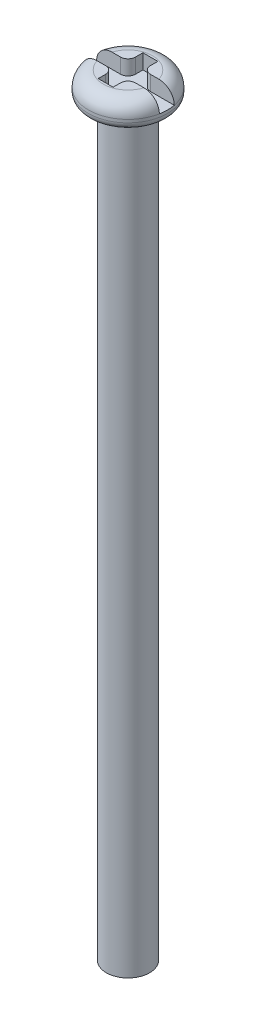
SolidWorks part; units mm, degrees
material "1060 合金"
ref_plane "前视基准面" through (0, 0, 0) normal (0, 0, 1) x (1, 0, 0)
ref_plane "上视基准面" through (0, 0, 0) normal (0, 1, 0) x (1, 0, 0)
ref_plane "右视基准面" through (0, 0, 0) normal (1, 0, 0) x (0, 0, -1)
sketch "草图1" plane through (0, 0, 0) normal (0, 1, 0) x (1, 0, 0)
  circle A0 centre (0, 0) radius 1.45
  dimension "D1" = 2.9
extrude "凸台-拉伸1" add sketch "草图1" along normal blind 50
cosmetic thread "装饰螺纹线1" parameters "D1"=49.5, "D2"=2.013
sketch "草图2" plane through (0, 50, 0) normal (0, 1, 0) x (1, 0, 0)
  circle A0 centre (0, 0) radius 2.65
  dimension "D1" = 5.3
extrude "凸台-拉伸2" add sketch "草图2" along normal blind 1.7
sketch "草图3" plane through (0, 51.7, 0) normal (0, 1, 0) x (1, 0, 0)
  line L1 (-3, 0.5) -> (3, 0.5)
  line L2 (-3, 0.5) -> (-3, -0.5)
  line L3 (-3, -0.5) -> (3, -0.5)
  line L4 (3, 0.5) -> (3, -0.5)
  line L5 (-3, 0.5) -> (3, -0.5) construction
  line L6 (-3, -0.5) -> (3, 0.5) construction
  line L7 (-0.5, 1.5) -> (0.5, 1.5)
  line L8 (-0.5, 1.5) -> (-0.5, -1.5)
  line L9 (-0.5, -1.5) -> (0.5, -1.5)
  line L10 (0.5, 1.5) -> (0.5, -1.5)
  line L11 (-0.5, 1.5) -> (0.5, -1.5) construction
  line L12 (-0.5, -1.5) -> (0.5, 1.5) construction
  point P0 (0, 0)
  point P6 (0, 0)
  circle M9 centre (0, 0) radius 2.65
  dimension "D1" = 1
  dimension "D2" = 6
  dimension "D3" = 1
  dimension "D4" = 3
extrude "切除-拉伸1" cut sketch "草图3" against normal blind 1 contours L8 L1 L3 M9 | L10 L7 L8 L1 | L10 L1 L8 L3 | L10 L3 L8 L9 | L1 L10 L3 M9
fillet "圆角1" radius 0.5 4 edges at (0.5, 51.2, -0.5) (0.5, 51.2, 0.5) (-0.5, 51.2, -0.5) (-0.5, 51.2, 0.5)
fillet "圆角2" radius 1 2 edges at (0, 51.7, -2.65) (0, 51.7, 2.65)
fillet "圆角3" radius 0.5 1 edges at (0, 50, 2.65)
